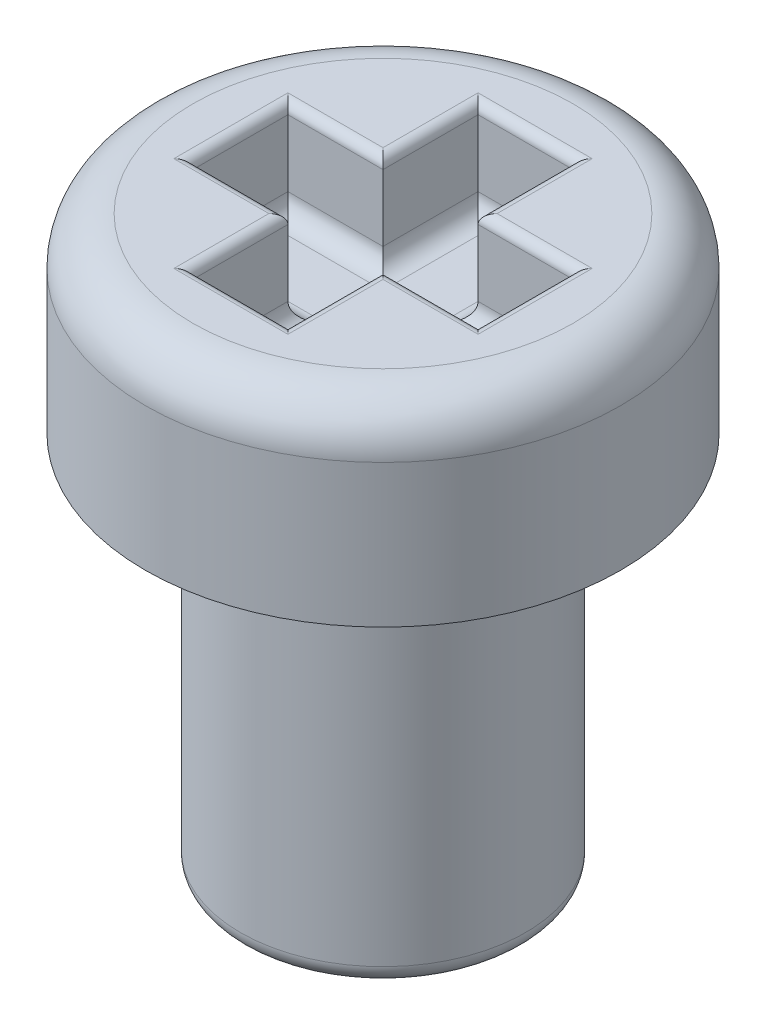
SolidWorks part; units mm, degrees
ref_plane "Front Plane" through (0, 0, 0) normal (0, 0, 1) x (1, 0, 0)
ref_plane "Top Plane" through (0, 0, 0) normal (0, 1, 0) x (1, 0, 0)
ref_plane "Right Plane" through (0, 0, 0) normal (1, 0, 0) x (0, 0, -1)
sketch "Sketch1" plane through (0, 0, 0) normal (0, 1, 0) x (1, 0, 0)
  circle A0 centre (0, 0) radius 1.5
  dimension "D1" = 3
extrude "Boss-Extrude1" add sketch "Sketch1" along normal blind 4
fillet "Fillet1" radius 0.2 1 edges at (0, 0, 1.5)
sketch "Sketch2" plane through (0, 0, 0) normal (0, 0, 1) x (1, 0, 0)
  line L0 (0, 0) -> (0, 13.199) construction
  line L1 (0, 4) -> (-2.5, 4)
  line L2 (1.5, 4) -> (-1.5, 4) construction
  line L3 (-2.5, 4) -> (-2.5, 6)
  line L4 (-2.5, 6) -> (0, 6)
  line L5 (0, 6) -> (0, 4)
  dimension "D1" = 2
  dimension "D2" = 2.5
revolve "Revolve1" add sketch "Sketch2" angle 360 about L0
sketch "Sketch3" plane through (0, 6, 0) normal (0, 1, 0) x (1, 0, 0)
  line L0 (0, -1003) -> (0, -1.5) construction
  line L1 (-1003, 0) -> (-1.5, 0) construction
  line L2 (-0.5, 0.5) -> (-1.5, 0.5)
  line L3 (-0.5, 1.5) -> (0.5, 1.5)
  line L4 (-0.5, 1.5) -> (-0.5, 0.5)
  line L5 (-0.5, -1.5) -> (0.5, -1.5)
  line L6 (0.5, 1.5) -> (0.5, 0.5)
  line L7 (0, -0.5) -> (0, 1.5) construction
  line L8 (-0.5, 0) -> (0.5, 0) construction
  line L9 (1.5, 0.5) -> (0.5, 0.5)
  line L10 (1.5, 0.5) -> (1.5, -0.5)
  line L11 (1.5, -0.5) -> (0.5, -0.5)
  line L12 (-1.5, 0.5) -> (-1.5, -0.5)
  line L13 (0, -0.5) -> (0, 0.5) construction
  line L14 (0.5, 0) -> (-0.5, 0) construction
  line L15 (-0.5, -0.5) -> (-0.5, -1.5)
  line L16 (-0.5, 0) -> (0.5, 0) construction
  line L17 (-0.5, -0.5) -> (-1.5, -0.5)
  line L18 (0, -0.5) -> (0, 50000) construction
  line L19 (0.5, -0.5) -> (0.5, -1.5)
  line L20 (1.5, 0) -> (50000, 0) construction
  point P5 (0, 0)
  point P9 (0, 0)
  dimension "D1" = 1
  dimension "D2" = 1
  dimension "D3" = 1
  dimension "D4" = 1
extrude "Cut-Extrude1" cut sketch "Sketch3" against normal blind 1
fillet "Fillet3" radius 0.1 12 edges at (-1, 6, 0.5) (-0.5, 6, 1) (0, 6, 1.5) (0.5, 6, 1) (1, 6, 0.5) (1.5, 6, 0) (1, 6, -0.5) (0.5, 6, -1) (0, 6, -1.5) (-0.5, 6, -1) (-1, 6, -0.5) (-1.5, 6, 0)
fillet "Fillet4" radius 0.2 12 edges at (-1, 5, -0.5) (-1.5, 5, 0) (-1, 5, 0.5) (-0.5, 5, 1) (0.5, 5, 1) (0, 5, 1.5) (1, 5, 0.5) (1.5, 5, 0) (1, 5, -0.5) (0.5, 5, -1) (0, 5, -1.5) (-0.5, 5, -1)
fillet "Fillet5" radius 0.5 1 edges at (0, 6, -2.5)
